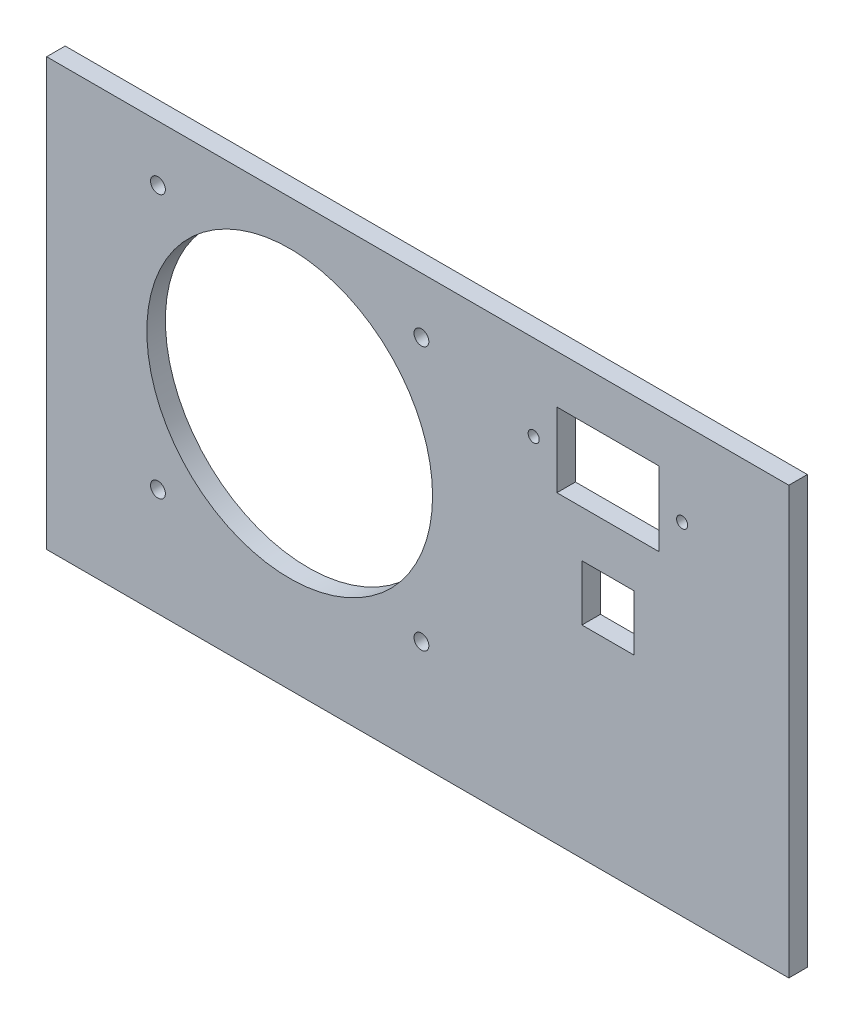
SolidWorks part; units mm, degrees
ref_plane "Front Plane" through (0, 0, 0) normal (0, 0, 1) x (1, 0, 0)
ref_plane "Top Plane" through (0, 0, 0) normal (0, 1, 0) x (1, 0, 0)
ref_plane "Right Plane" through (0, 0, 0) normal (1, 0, 0) x (0, 0, -1)
sketch "Sketch1" plane through (0, 0, 0) normal (0, 0, 1) x (1, 0, 0)
  line L0 (-100, 7) -> (100, 7) construction
  line L1 (-100, -57.5) -> (100, -57.5)
  line L2 (-100, -57.5) -> (-100, 57.5)
  line L3 (-100, 57.5) -> (100, 57.5)
  line L4 (100, -57.5) -> (100, 57.5)
  line L5 (-100, -57.5) -> (100, 57.5) construction
  line L6 (-100, 57.5) -> (100, -57.5) construction
  line L7 (-34.5, -57.5) -> (-34.5, 57.5) construction
  line L8 (-34.5, 7) -> (-70, 42.5) construction
  line L9 (-34.5, 7) -> (1, 42.5) construction
  line L10 (100, 34.5) -> (-18.9664, 34.5) construction
  line L11 (51.25, 56.1033) -> (51.25, 1.2979) construction
  line L12 (25.145, -35.5484) -> (25.145, -36.5) construction
  line L13 (37.5, 24.5) -> (65, 24.5)
  line L14 (37.5, 24.5) -> (37.5, 44.5)
  line L15 (37.5, 44.5) -> (65, 44.5)
  line L16 (65, 24.5) -> (65, 44.5)
  line L17 (37.5, 24.5) -> (65, 44.5) construction
  line L18 (37.5, 44.5) -> (65, 24.5) construction
  line L22 (44.25, 12) -> (58.25, 12)
  line L23 (44.25, 12) -> (44.25, -3)
  line L24 (44.25, -3) -> (58.25, -3)
  line L25 (58.25, 12) -> (58.25, -3)
  line L26 (44.25, 12) -> (58.25, -3) construction
  line L27 (44.25, -3) -> (58.25, 12) construction
  circle A0 centre (-34.5, 7) radius 38.5
  circle A1 centre (-70, 42.5) radius 2
  circle A2 centre (1, 42.5) radius 2
  circle A3 centre (1, -28.5) radius 2
  circle A4 centre (-70, -28.5) radius 2
  circle A5 centre (71.25, 34.5) radius 1.5
  circle A6 centre (31.25, 34.5) radius 1.5
  point P0 (0, 0)
  point P23 (-5, -25)
  point P27 (51.25, 4.5)
  point P28 (51.25, 34.5)
  point P39 (0, 0)
  point P40 (0, 0)
  point P56 (0, 0)
  point P57 (0, 0)
  dimension "D3" = 77
  dimension "D4" = 4
  dimension "D9" = 4
  dimension "D15" = 3
  dimension "D1" = 200
  dimension "D2" = 115
  dimension "D5" = 35.5
  dimension "D6" = 35.5
  dimension "D7" = 65.5
  dimension "D8" = 64.5
  dimension "D10" = 90
  dimension "D11" = 27.5
  dimension "D12" = 20
  dimension "D13" = 13
  dimension "D14" = 35
  dimension "D16" = 20
  dimension "D17" = 15
  dimension "D18" = 30
  dimension "D27" = 14
  dimension "D28" = 15
  dimension "D29" = 30
extrude "Boss-Extrude1" add sketch "Sketch1" along normal blind 5
